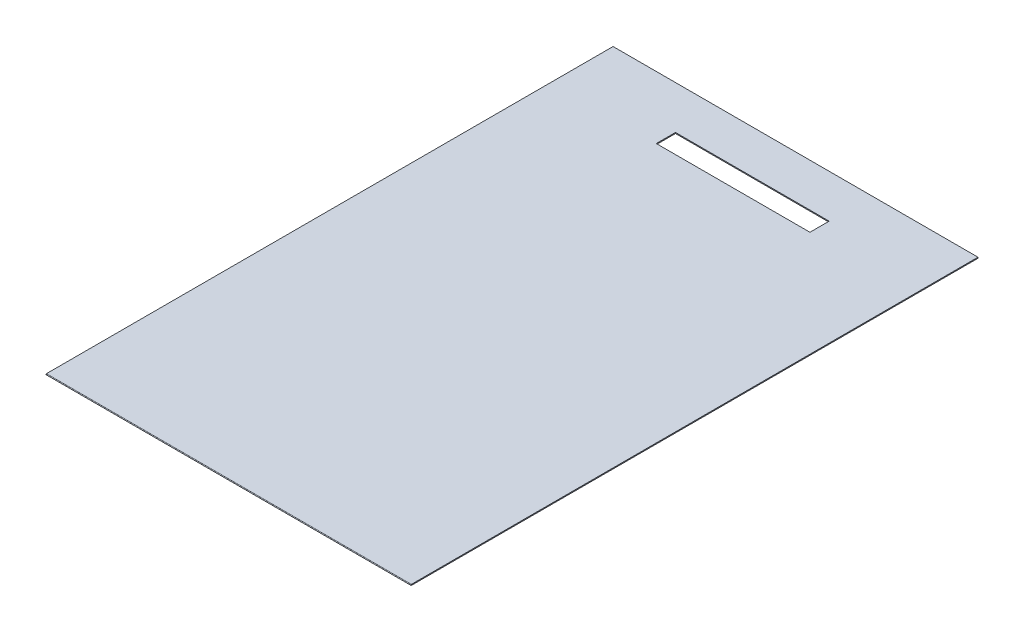
SolidWorks part; units mm, degrees
ref_plane "Front Plane" through (0, 0, 0) normal (0, 0, 1) x (1, 0, 0)
ref_plane "Top Plane" through (0, 0, 0) normal (0, 1, 0) x (1, 0, 0)
ref_plane "Right Plane" through (0, 0, 0) normal (1, 0, 0) x (0, 0, -1)
sketch "Sketch1" plane through (0, 0, 0) normal (0, 1, 0) x (1, 0, 0)
  line L1 (-95, -147.5) -> (95, -147.5)
  line L2 (-95, -147.5) -> (-95, 147.5)
  line L3 (-95, 147.5) -> (95, 147.5)
  line L4 (95, -147.5) -> (95, 147.5)
  line L5 (-95, -147.5) -> (95, 147.5) construction
  line L6 (-95, 147.5) -> (95, -147.5) construction
  line L7 (-40, 125) -> (40, 125)
  line L8 (-40, 125) -> (-40, 115)
  line L9 (-40, 115) -> (40, 115)
  line L10 (40, 125) -> (40, 115)
  line L11 (-40, 125) -> (40, 115) construction
  line L12 (-40, 115) -> (40, 125) construction
  point P0 (0, 0)
  point P6 (0, 120)
  point P11 (0, 0)
  dimension "D1" = 295
  dimension "D2" = 190
  dimension "D3" = 10
  dimension "D4" = 80
  dimension "D5" = 120
extrude "Boss-Extrude1" add sketch "Sketch1" along normal blind 0.5
sketch "Sketch2" plane through (95, 0, 0) normal (1, 0, 0) x (0, 0, -1)
  line L0 (-147.5, 0.5) -> (-147.5, 0) construction
  line L1 (-147.5, 0.5) -> (-147.5, 0)
  arc A0 (-147.5, 0.5) -> (-147.5, 0) centre (-147.5, 0.25) ccw
extrude "Boss-Extrude2" add sketch "Sketch2" against normal blind 190
